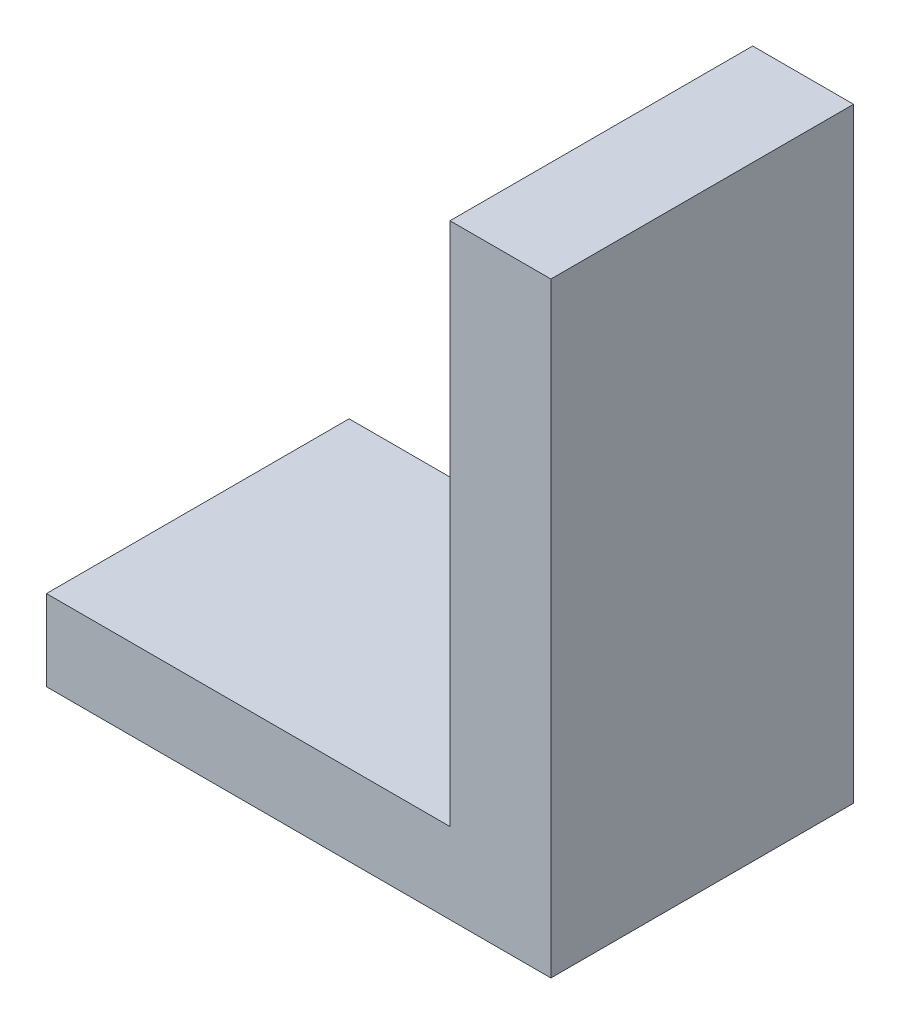
SolidWorks part; units mm, degrees
ref_plane "Alzado" through (0, 0, 0) normal (0, 0, 1) x (1, 0, 0)
ref_plane "Planta" through (0, 0, 0) normal (0, 1, 0) x (1, 0, 0)
ref_plane "Vista lateral" through (0, 0, 0) normal (1, 0, 0) x (0, 0, -1)
sketch "Croquis_perfil_L" plane through (0, 0, 0) normal (0, 0, 1) x (1, 0, 0)
  line L0 (-62.5, 0) -> (62.5, 0)
  line L1 (62.5, 0) -> (62.5, 150)
  line L2 (62.5, 150) -> (37.5, 150)
  line L3 (37.5, 150) -> (37.5, 20)
  line L4 (37.5, 20) -> (-62.5, 20)
  line L5 (-62.5, 20) -> (-62.5, 0)
  dimension "D1" = 100
  dimension "D2" = 125
  dimension "D3" = 20
  dimension "D4" = 150
extrude "Angulo_L" add sketch "Croquis_perfil_L" along normal mid plane 75
sketch "Croquis_agujeros_montaje" plane through (0, 0, 0) normal (0, 1, 0) x (1, 0, 0)
  circle A0 centre (-50, 0) radius 5
  circle A1 centre (0, 0) radius 5
  dimension "D1" = 10
  dimension "D2" = 50
extrude "Agujero_inserto_M6" cut sketch "Croquis_agujeros_montaje" along normal blind 14
